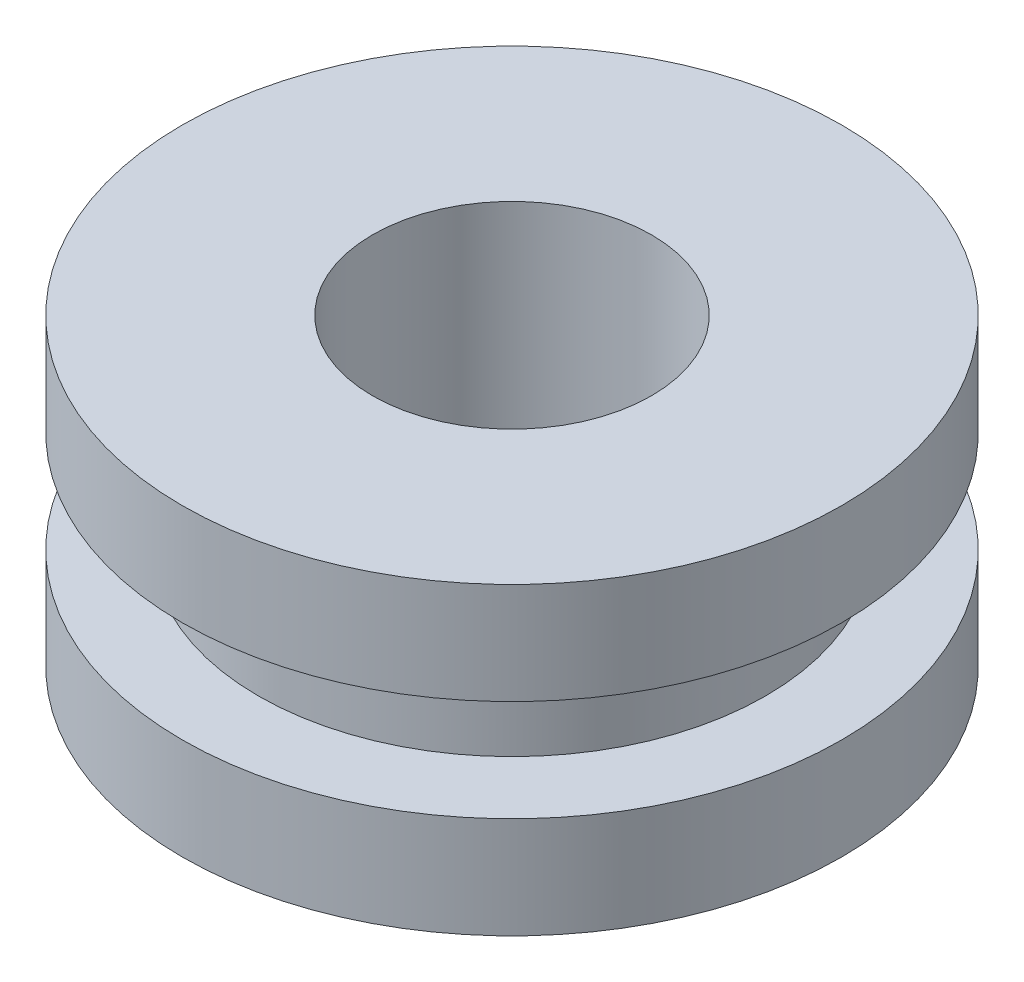
SolidWorks part; units mm, degrees
ref_plane "Ebene vorne" through (0, 0, 0) normal (0, 0, 1) x (1, 0, 0)
ref_plane "Ebene oben" through (0, 0, 0) normal (0, 1, 0) x (1, 0, 0)
ref_plane "Ebene rechts" through (0, 0, 0) normal (1, 0, 0) x (0, 0, -1)
sketch "Skizze1" plane through (0, 0, 0) normal (0, 1, 0) x (1, 0, 0)
  circle A0 centre (0, 0) radius 6.5
  dimension "D1" = 13
extrude "Aufsatz-Linear austragen1" add sketch "Skizze1" along normal blind 2
sketch "Skizze2" plane through (0, 2, 0) normal (0, 1, 0) x (1, 0, 0)
  circle A0 centre (0, 0) radius 5
  dimension "D1" = 10
extrude "Aufsatz-Linear austragen2" add sketch "Skizze2" along normal blind 1
mirror "Spiegeln3" about plane through (0, 3, 0) normal (0, 1, 0) of "Aufsatz-Linear austragen2"
sketch "Skizze3" plane through (0, 4, 0) normal (0, 1, 0) x (1, 0, 0)
  circle A0 centre (0, 0) radius 6.5
  dimension "D1" = 13
extrude "Aufsatz-Linear austragen3" add sketch "Skizze3" along normal blind 2
hole_wizard "Durchgangsloch für M51" positions "Skizze4" profile "Skizze5" hole size "M5" standard "DIN" end condition up to next
sketch "Skizze4" plane through (0, 6, 0) normal (0, 1, 0) x (1, 0, 0)
  point P0 (0, 0)
sketch "Skizze5" plane through (0, 6, 0) normal (1, 0, 0) x (0, 0, 1)
  line L0 (0, 0) -> (0, 6)
  line L1 (0, 6) -> (2.75, 6)
  line L2 (2.75, 6) -> (2.75, 0)
  line L5 (2.75, 0) -> (0, 0)
  line L11 (0, -6.35) -> (0, 107.95) construction
  dimension "Bohrerdurchmesser" = 5.5
  dimension "Bohrungstiefe" = 6
